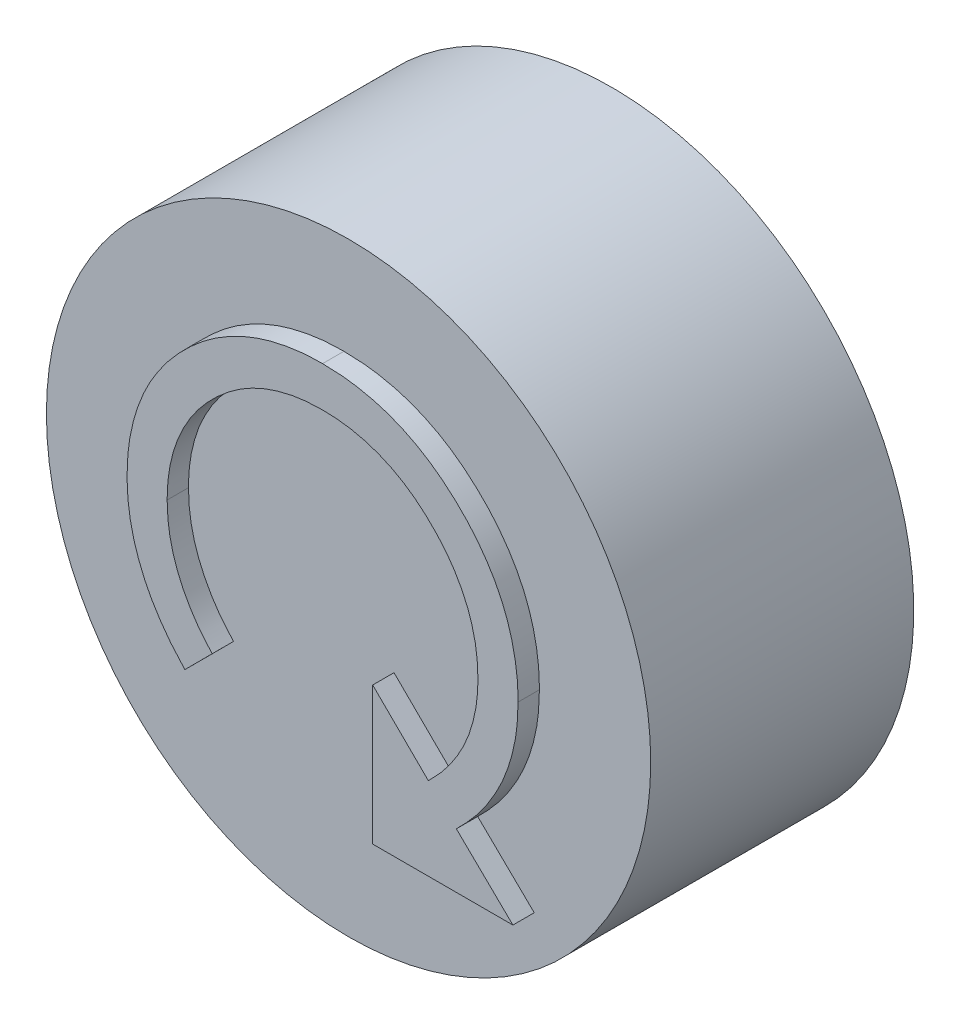
SolidWorks part; units mm, degrees
ref_plane "Front Plane" through (0, 0, 0) normal (0, 0, 1) x (1, 0, 0)
ref_plane "Top Plane" through (0, 0, 0) normal (0, 1, 0) x (1, 0, 0)
ref_plane "Right Plane" through (0, 0, 0) normal (1, 0, 0) x (0, 0, -1)
sketch "Sketch1" plane through (0, 0, 0) normal (0, 0, 1) x (1, 0, 0)
  circle A0 centre (0, 0) radius 8.5
  dimension "D1" = 17
extrude "Boss-Extrude1" add sketch "Sketch1" along normal blind 4.4
sketch "Sketch2" plane through (0, 0, 4.4) normal (0, 0, 1) x (1, 0, 0)
  line L19 (6.6377, 5.6994) -> (-3.7876, 5.6994) construction
  text T0 "P" font "Wingdings 3" height 11
  point P0 (6.6377, 5.6994)
  point P7 (3.2424, 1.1561)
  point P8 (6.4099, 5.3898)
  point P9 (0, 0)
  point P10 (7.712, 5.2328)
  point P11 (0, 0)
  point P12 (0, 0)
sketch "Sketch3" plane through (0, 0, 0) normal (0, 0, -1) x (-1, 0, 0)
  circle A0 centre (0, 0) radius 5.8
  dimension "D1" = 11.6
extrude "Cut-Extrude1" cut sketch "Sketch3" against normal blind 4
sketch "Sketch4" plane through (0, 0, 0) normal (0, 0, -1) x (-1, 0, 0)
  circle A1 centre (0, 0) radius 8.5
  circle A2 centre (0, 0) radius 8.5
  circle A4 centre (0, 0) radius 7.5
  dimension "D2" = 1
  dimension "D1" = 0
extrude "Boss-Extrude3" add sketch "Sketch4" along normal blind 3
sketch "Sketch6" plane through (0, 0, 0) normal (0, 1, 0) x (1, 0, 0)
  line L6 (7.5, 0) -> (5.8, -1.7)
  line L7 (5.8, -1.7) -> (5.8, 0)
  line L8 (5.8, 0) -> (7.5, 0)
  line L9 (7.5, 0) -> (-7.5, 0) construction
  line L10 (5.8, 0) -> (-5.8, 0) construction
  dimension "D1" = 45
ref_axis "Axis1" through (0, 0, -5.5) along (0, 0, 1)
revolve "Cut-Revolve1" cut sketch "Sketch6" angle 360 about axis through (0, 0, -5.5) along (0, 0, 1)
extrude "Boss-Extrude4" add sketch "Sketch2" along normal blind 0.6
